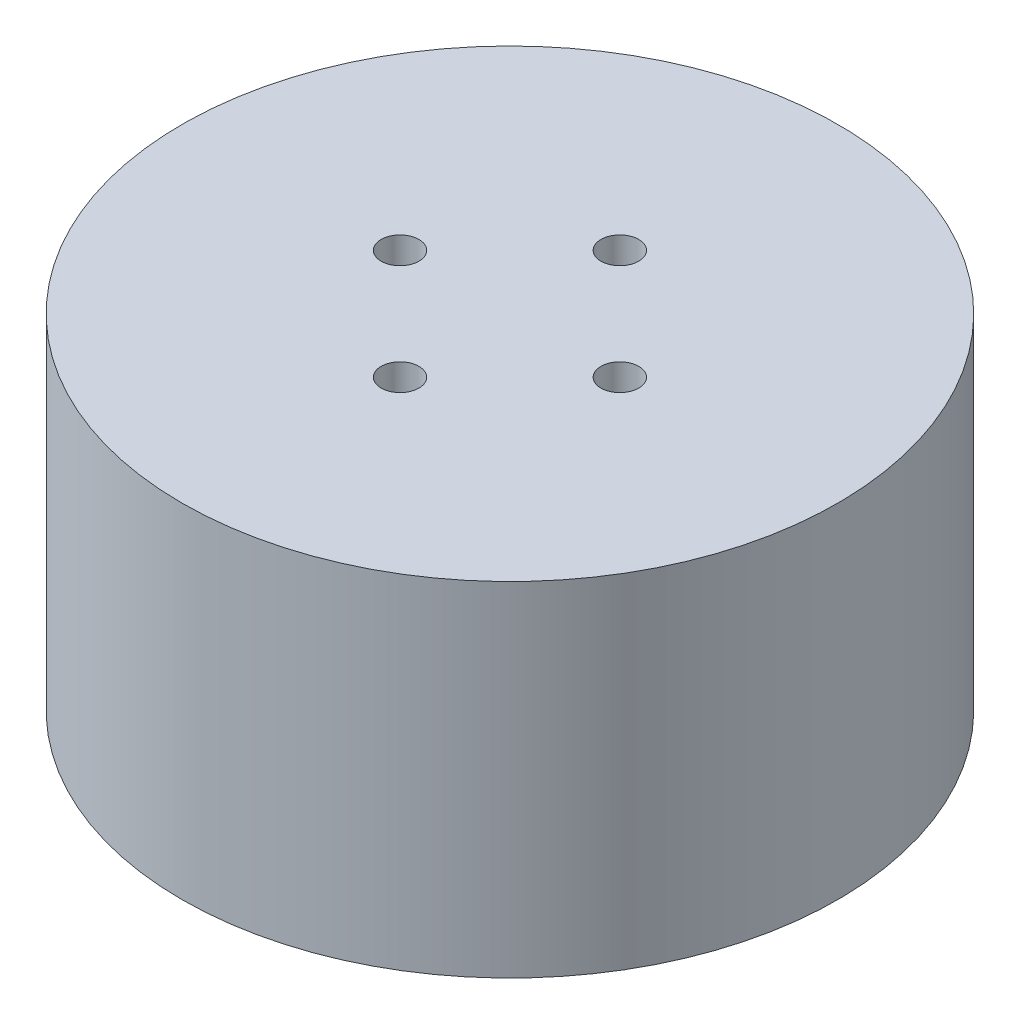
SolidWorks part; units mm, degrees
ref_plane "Plan de face" through (0, 0, 0) normal (0, 0, 1) x (1, 0, 0)
ref_plane "Plan de dessus" through (0, 0, 0) normal (0, 1, 0) x (1, 0, 0)
ref_plane "Plan de droite" through (0, 0, 0) normal (1, 0, 0) x (0, 0, -1)
sketch "Esquisse1" plane through (0, 0, 0) normal (0, 1, 0) x (1, 0, 0)
  circle A0 centre (0, 0) radius 47.75
  dimension "D1" = 95.5
extrude "Boss.-Extru.1" add sketch "Esquisse1" along normal blind 50
sketch "Esquisse2" plane through (0, 0, 0) normal (0, -1, 0) x (-1, 0, 0)
  circle A0 centre (0, 0) radius 26
extrude "Enlèv. mat.-Extru.1" cut sketch "Esquisse2" against normal blind 20
sketch "Esquisse3" plane through (0, 20, 0) normal (0, -1, 0) x (-1, 0, 0)
  circle A0 centre (0, 0) radius 11
  dimension "D1" = 22
extrude "Enlèv. mat.-Extru.5" cut sketch "Esquisse3" against normal blind 7.5
sketch "Esquisse4" plane through (0, 27.5, 0) normal (0, -1, 0) x (-1, 0, 0)
  circle A0 centre (0, 0) radius 5
  dimension "D1" = 10
extrude "Enlèv. mat.-Extru.6" cut sketch "Esquisse4" against normal blind 13.5
sketch "Esquisse5" plane through (0, 50, 0) normal (0, 1, 0) x (1, 0, 0)
  line L0 (-26, 0) -> (26, 0)
  line L1 (0, 26) -> (0, -26)
  circle A0 centre (0, 0) radius 26
  point P7 (0, 0)
  point P8 (-16, 0)
  point P9 (0, 16)
  point P10 (16, 0)
  point P11 (0, -16)
  point P12 (0, 0)
  dimension "D1" = 52
sketch "Esquisse11" plane through (0, 50, 0) normal (0, 1, 0) x (1, 0, 0)
  circle A0 centre (-16, 0) radius 2.75
  circle A1 centre (0, 16) radius 2.75
  circle A2 centre (16, 0) radius 2.75
  circle A3 centre (0, -16) radius 2.75
  dimension "D1" = 5.5
  dimension "D2" = 5.5
  dimension "D3" = 5.5
  dimension "D4" = 5.5
extrude "Enlèv. mat.-Extru.11" cut sketch "Esquisse11" against normal through all
ref_plane "Plan1" through (-47.75, 0, 0) normal (-1, 0, 0) x (0, 0, 1)
ref_plane "Plan2" through (47.75, 0, 0) normal (1, 0, 0) x (0, 0, -1)
